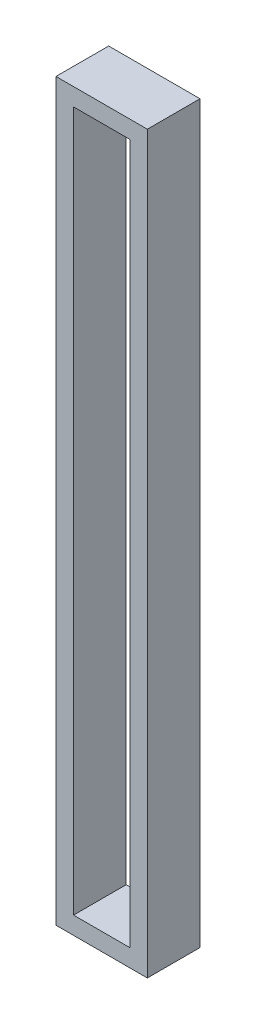
SolidWorks part; units mm, degrees
ref_plane "Front Plane" through (0, 0, 0) normal (1, 0, 0) x (0, 1, 0)
ref_plane "Top Plane" through (0, 0, 0) normal (0, 0, 1) x (0, 1, 0)
ref_plane "Right Plane" through (0, 0, 0) normal (0, 1, 0) x (-1, 0, 0)
sketch "Sketch1" plane through (0, 0, 0) normal (0, 0, 1) x (0, 1, 0)
  line L1 (0, 0) -> (39.84, 0)
  line L2 (0, 0) -> (0, 3.2)
  line L3 (0, 3.2) -> (39.84, 3.2)
  line L4 (39.84, 0) -> (39.84, 3.2)
  line L5 (-1, 4.2) -> (40.84, 4.2)
  line L6 (-1, 4.2) -> (-1, -1)
  line L7 (-1, -1) -> (40.84, -1)
  line L8 (40.84, 4.2) -> (40.84, -1)
  point P9 (0, 1.6)
  point P10 (-1, 1.6)
  point P11 (19.92, 0)
  point P12 (19.92, -1)
  dimension "D2" = 39.84
  dimension "D1" = 3.2
  dimension "D4" = 1
  dimension "D3" = 1
extrude "Boss-Extrude1" add sketch "Sketch1" along normal blind 3
equation "\"cable width\"= .2in"
equation "\"clearance\"= 0.2mm"
equation "\"slot_width\"= \"cable width\" + \"clearance\""
equation "\"base\"= ( \"slot_width\" ) * 3 + 4 * ( 6 )"
equation "\"depth\" = 40mm"
equation "\"thick\"= 3mm"
equation "\"avg_t_wood\"= 2.74mm"
equation "\"ideal_t_wood\"= 3mm"
equation "\"kerf\"= 0.2mm"
equation "\"slot_height\"= \"avg_t_wood\" + \"kerf\""
equation "\"wood_slot_width\"= 10mm + \"kerf\""
equation "\"wood_slot_clearance\"= - .2mm"
equation "\"woodstand_width\"= 10mm"
equation "\"woodstand_length\" = 75mm"
equation "\"D2@Sketch1\"=\"base\""
equation "\"D1@Sketch1\"=\"thick\"+\"clearance\""
equation "\"D1@Boss-Extrude1\"=\"thick\""
